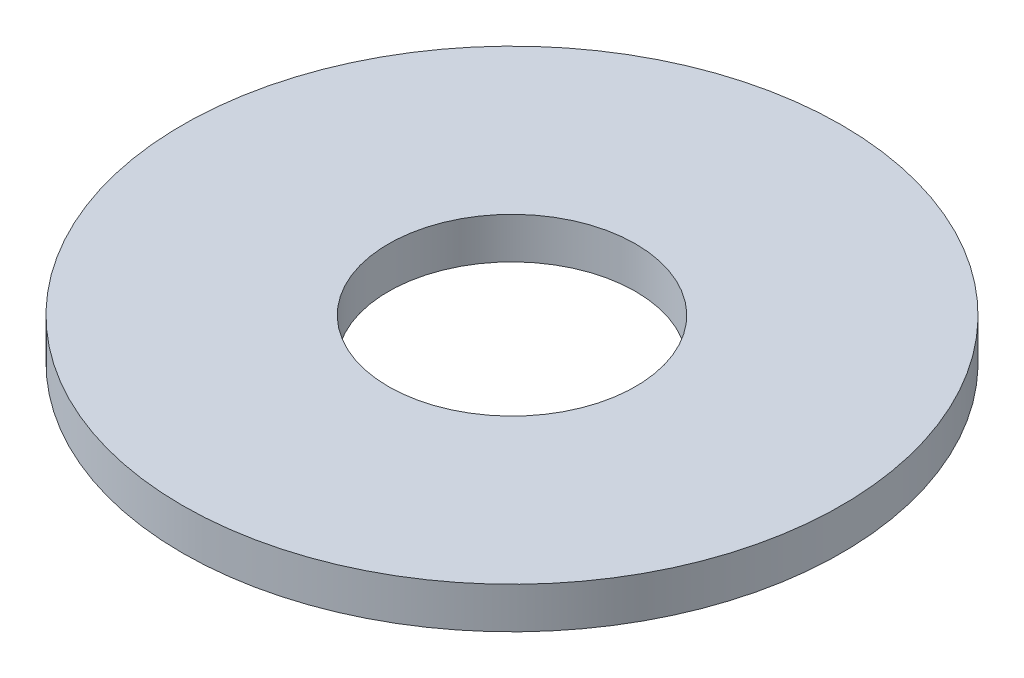
SolidWorks part; units mm, degrees
material "AISI 304"
ref_plane "前视基准面" through (0, 0, 0) normal (0, 0, 1) x (1, 0, 0)
ref_plane "上视基准面" through (0, 0, 0) normal (0, 1, 0) x (1, 0, 0)
ref_plane "右视基准面" through (0, 0, 0) normal (1, 0, 0) x (0, 0, -1)
other "Configuration Table"
sketch "草图1" plane through (0, 0, 0) normal (0, 1, 0) x (1, 0, 0)
  circle A0 centre (0, 0) radius 4
  circle A1 centre (0, 0) radius 1.5
  dimension "D1" = 3
  dimension "D2" = 8
extrude "凸台-拉伸1" add sketch "草图1" along normal blind 0.5
